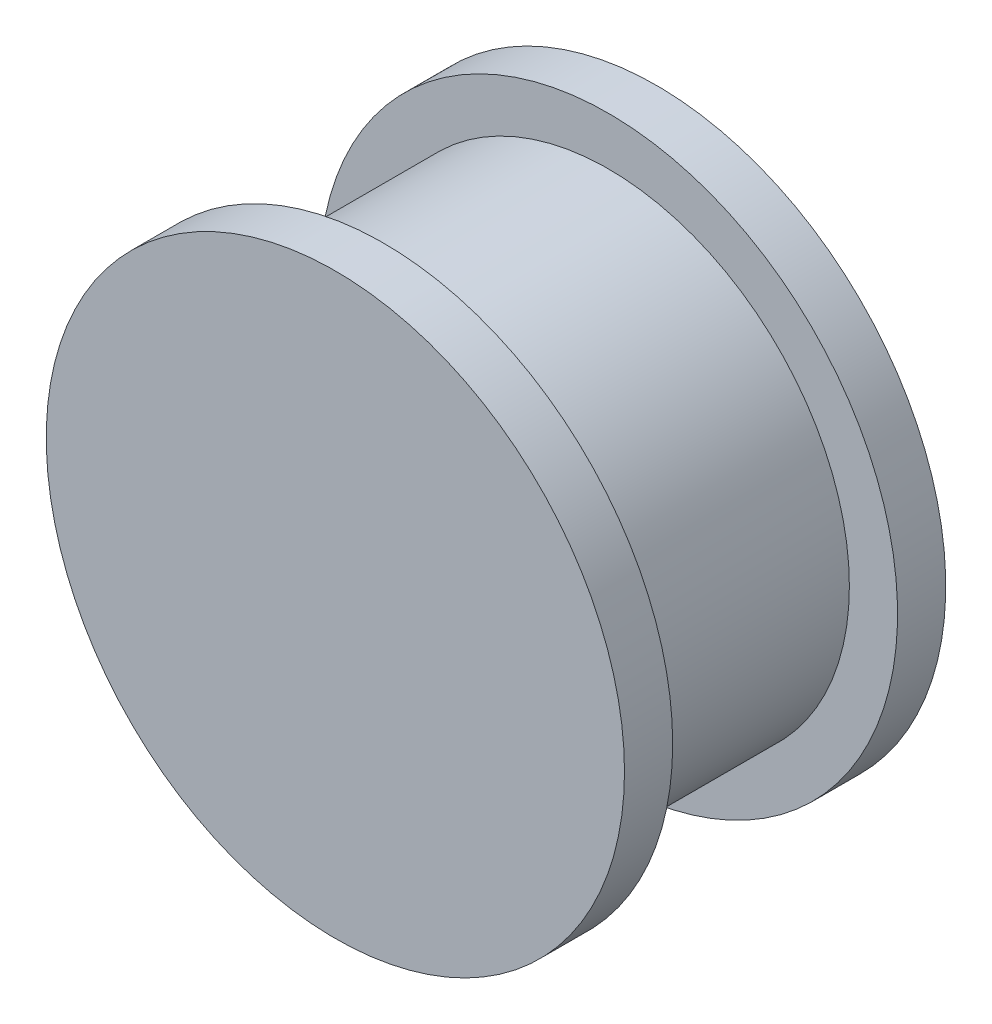
SolidWorks part; units mm, degrees
ref_plane "Front Plane" through (0, 0, 0) normal (0, 0, 1) x (1, 0, 0)
ref_plane "Top Plane" through (0, 0, 0) normal (0, 1, 0) x (1, 0, 0)
ref_plane "Right Plane" through (0, 0, 0) normal (1, 0, 0) x (0, 0, -1)
sketch "Sketch1" plane through (0, 0, 0) normal (0, 0, 1) x (1, 0, 0)
  circle A0 centre (0, 0) radius 6.5
  circle A1 centre (0, 0) radius 7.5
  dimension "D1" = 13
  dimension "D2" = 1
extrude "Boss-Extrude2" add sketch "Sketch1" along normal blind 7
sketch "Sketch3" plane through (0, 0, 7) normal (0, 0, 1) x (1, 0, 0)
  circle A0 centre (0, 0) radius 9
  dimension "D1" = 18
extrude "Boss-Extrude3" add sketch "Sketch3" along normal blind 1.5
sketch "Sketch4" plane through (0, 0, 0) normal (0, 0, -1) x (-1, 0, 0)
  circle A0 centre (0, 0) radius 6.5
  circle A1 centre (0, 0) radius 9
  circle A2 centre (0, 0) radius 6.5 construction
extrude "Boss-Extrude4" add sketch "Sketch4" along normal blind 1.5 separate body
